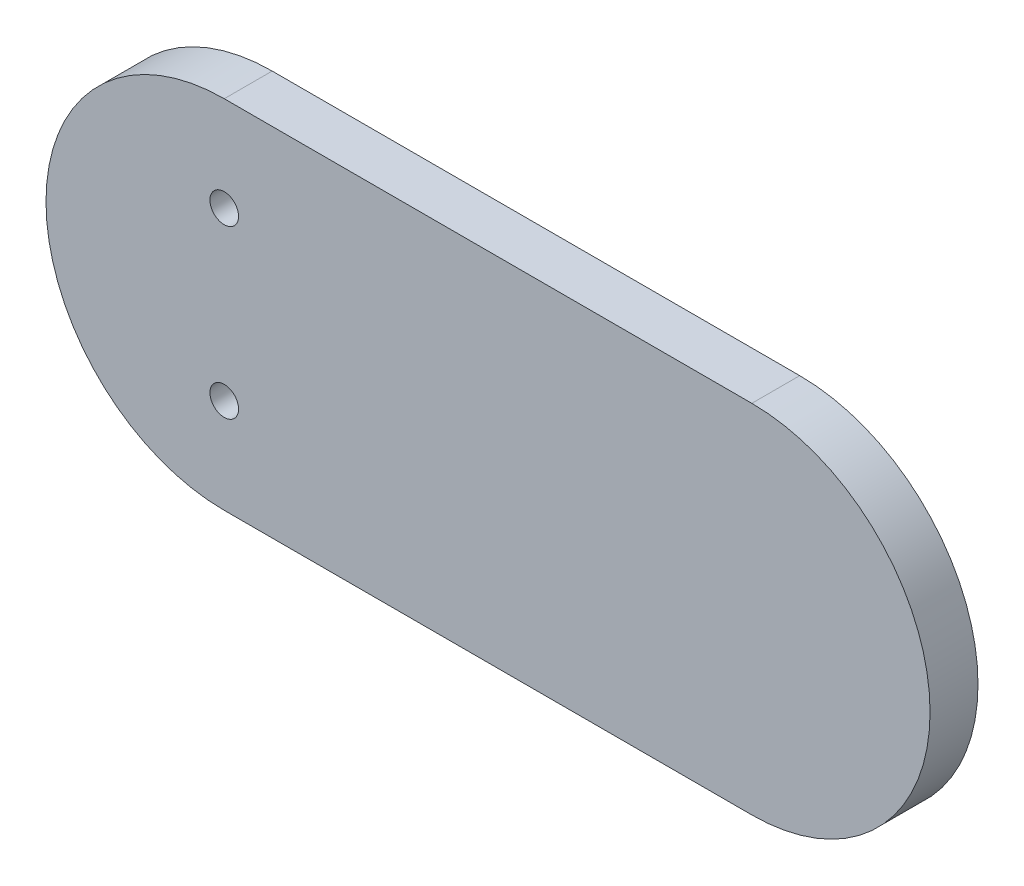
SolidWorks part; units mm, degrees
ref_plane "Front Plane" through (0, 0, 0) normal (0, 0, 1) x (1, 0, 0)
ref_plane "Top Plane" through (0, 0, 0) normal (0, 1, 0) x (1, 0, 0)
ref_plane "Right Plane" through (0, 0, 0) normal (1, 0, 0) x (0, 0, -1)
sketch "Sketch3" plane through (0, 0, 0) normal (0, 0, 1) x (1, 0, 0)
  line L0 (-17.5, 0) -> (17.5, 0) construction
  line L1 (-17.5, 11.825) -> (17.5, 11.825)
  line L2 (-17.5, -11.825) -> (17.5, -11.825)
  arc A0 (-17.5, 11.825) -> (-17.5, -11.825) centre (-17.5, 0) ccw
  arc A1 (17.5, -11.825) -> (17.5, 11.825) centre (17.5, 0) ccw
  point P2 (0, 0)
  dimension "D2" = 11.825
  dimension "D1" = 35
extrude "Boss-Extrude1" add sketch "Sketch3" along normal mid plane 3.18
sketch "Sketch4" plane through (0, 0, 1.59) normal (0, 0, 1) x (1, 0, 0)
  line L0 (-17.5, 11.825) -> (-17.5, -11.825) construction
  line L1 (0, 0) -> (-23.1703, 0) construction
  circle A0 centre (-17.5, 5.535) radius 0.95
  circle A1 centre (-17.5, -5.535) radius 0.95
  arc A2 (-17.5, 11.825) -> (-17.5, -11.825) centre (-17.5, 0) ccw construction
  point P13 (0, 0)
  point P14 (0, 0)
  dimension "D1" = 1.9
  dimension "D2" = 11.07
extrude "Cut-Extrude1" cut sketch "Sketch4" against normal blind 10
